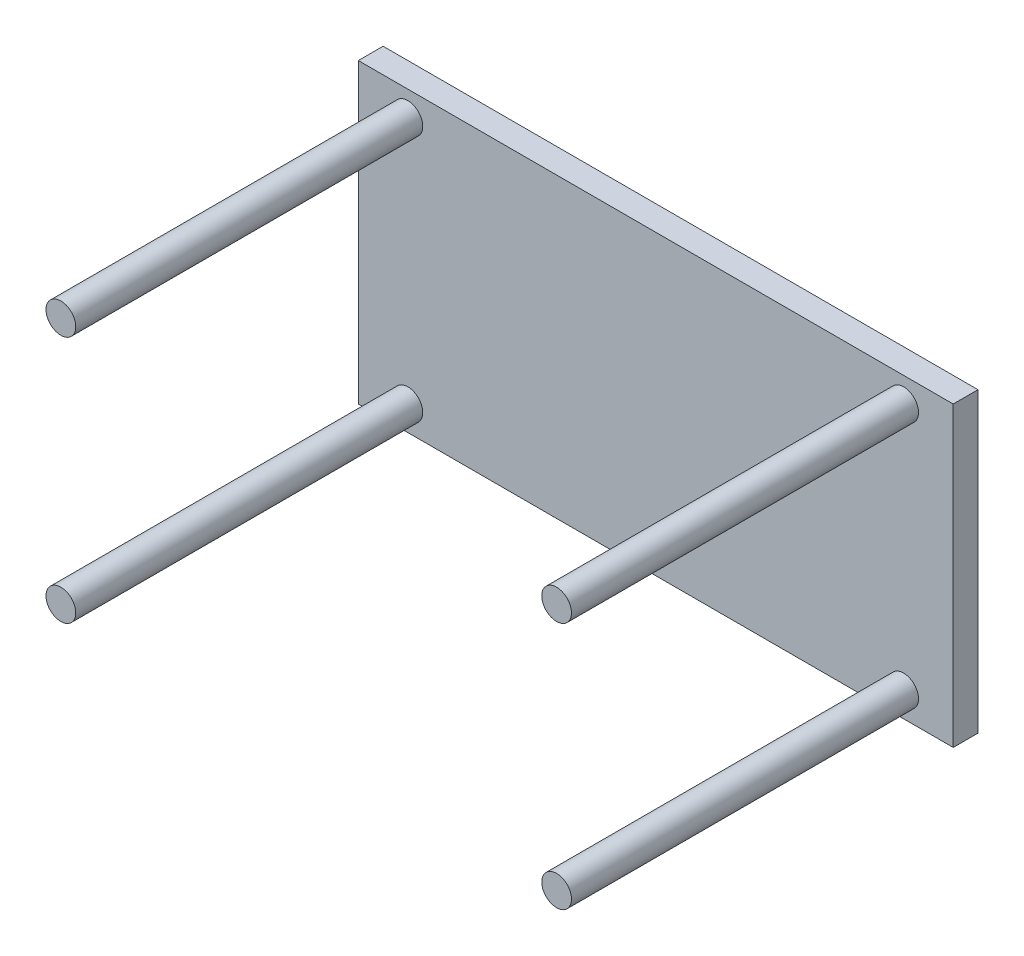
SolidWorks part; units mm, degrees
ref_plane "前视基准面" through (0, 0, 0) normal (0, 0, 1) x (1, 0, 0)
ref_plane "上视基准面" through (0, 0, 0) normal (0, 1, 0) x (1, 0, 0)
ref_plane "右视基准面" through (0, 0, 0) normal (1, 0, 0) x (0, 0, -1)
other "Configuration Table"
sketch "草图1" plane through (0, 0, 0) normal (0, 0, 1) x (1, 0, 0)
  line L1 (-600, -300) -> (600, -300)
  line L2 (-600, -300) -> (-600, 300)
  line L3 (-600, 300) -> (600, 300)
  line L4 (600, -300) -> (600, 300)
  line L5 (-600, -300) -> (600, 300) construction
  line L6 (-600, 300) -> (600, -300) construction
  point P0 (0, 0)
extrude "凸台-拉伸1" add sketch "草图1" along normal blind 50
sketch "草图2" plane through (0, 0, 0) normal (0, 0, 1) x (1, 0, 0)
  circle A0 centre (-500, -250) radius 30
extrude "凸台-拉伸2" add sketch "草图2" along normal blind 750
sketch "草图3" plane through (0, 0, 0) normal (0, 0, 1) x (1, 0, 0)
  circle A0 centre (500, -250) radius 30
extrude "凸台-拉伸3" add sketch "草图3" along normal blind 750
sketch "草图4" plane through (0, 0, 0) normal (0, 0, 1) x (1, 0, 0)
  circle A0 centre (-500, 250) radius 30
extrude "凸台-拉伸4" add sketch "草图4" along normal blind 750
sketch "草图5" plane through (0, 0, 0) normal (0, 0, 1) x (1, 0, 0)
  circle A0 centre (500, 250) radius 30
extrude "凸台-拉伸5" add sketch "草图5" along normal blind 750
